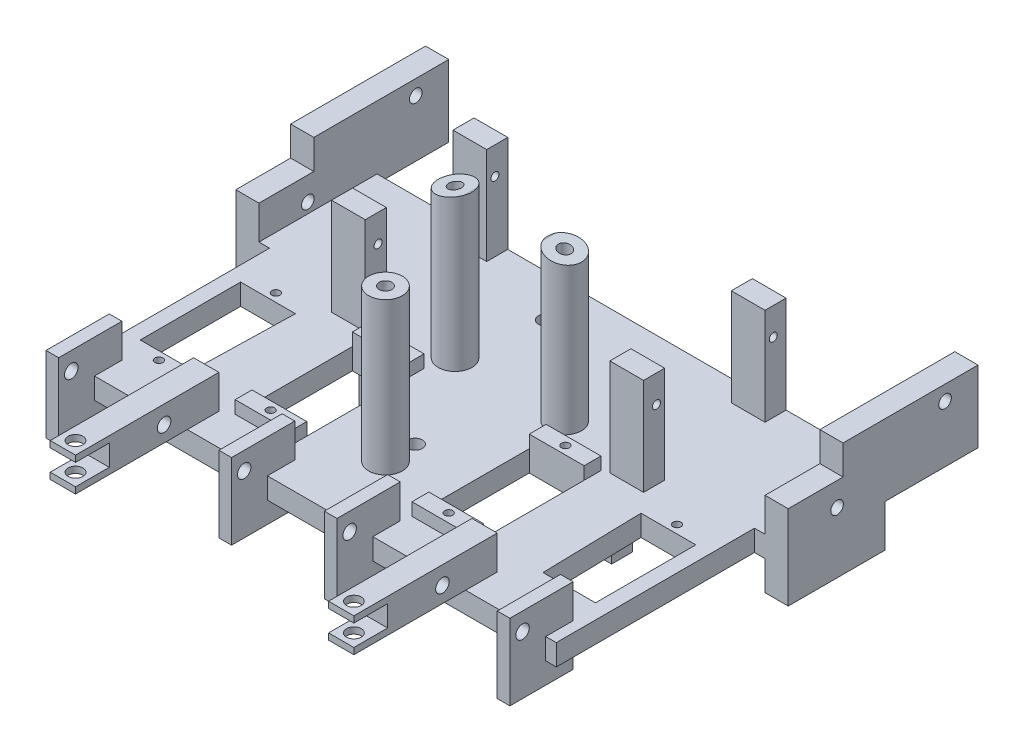
SolidWorks part; units mm, degrees
material "PMMA"
ref_plane "前视基准面" through (0, 0, 0) normal (0, 0, 1) x (1, 0, 0)
ref_plane "上视基准面" through (0, 0, 0) normal (0, 1, 0) x (1, 0, 0)
ref_plane "右视基准面" through (0, 0, 0) normal (1, 0, 0) x (0, 0, -1)
sketch "草图1" plane through (0, 0, 0) normal (0, 1, 0) x (1, 0, 0)
  line L1 (-57.5, 37.5) -> (57.5, 37.5)
  line L2 (-57.5, 37.5) -> (-57.5, -37.5)
  line L3 (-57.5, -37.5) -> (57.5, -37.5)
  line L4 (57.5, 37.5) -> (57.5, -37.5)
  line L5 (-57.5, 37.5) -> (57.5, -37.5) construction
  line L6 (-57.5, -37.5) -> (57.5, 37.5) construction
  point P0 (0, 0)
  dimension "D1" = 115
  dimension "D2" = 75
extrude "凸台-拉伸1" add sketch "草图1" along normal blind 5
sketch "草图4" plane through (0, 5, 0) normal (0, 1, 0) x (1, 0, 0)
  line L1 (-60, 9.5) -> (60, 9.5)
  line L2 (-60, 9.5) -> (-60, 37.5)
  line L3 (-60, 37.5) -> (60, 37.5)
  line L4 (60, 9.5) -> (60, 37.5)
  line L5 (-60, 9.5) -> (60, 37.5) construction
  line L6 (-60, 37.5) -> (60, 9.5) construction
  line L7 (-57.5, -37.5) -> (57.5, -37.5) construction
  point P0 (0, 23.5)
  dimension "D1" = 120
  dimension "D2" = 28
  dimension "D3" = 75
extrude "凸台-拉伸4" add sketch "草图4" against normal blind 5
sketch "草图5" plane through (-60, 0, 0) normal (-1, 0, 0) x (0, 0, 1)
  line L0 (-37.5, 5) -> (-9.5, 5) construction
  line L1 (-9.5, 13) -> (-32.5, 13)
  line L2 (-9.5, 13) -> (-9.5, -7)
  line L3 (-9.5, -7) -> (-32.5, -7)
  line L4 (-32.5, 13) -> (-32.5, -7)
  line L5 (-9.5, 5) -> (-9.5, 0) construction
  dimension "D1" = 8
  dimension "D2" = 23
  dimension "D3" = 20
extrude "凸台-拉伸5" add sketch "草图5" along normal blind 5.5
sketch "草图6" plane through (-60, 0, 0) normal (-1, 0, 0) x (0, 0, 1)
  line L1 (-54.5, 20) -> (-22.5, 20)
  line L2 (-54.5, 20) -> (-54.5, 3)
  line L3 (-54.5, 3) -> (-22.5, 3)
  line L4 (-22.5, 20) -> (-22.5, 3)
  line L5 (-37.5, 5) -> (-32.5, 5) construction
  line L6 (-37.5, 0) -> (-37.5, 5) construction
  dimension "D1" = 15
  dimension "D2" = 17
  dimension "D3" = 32
  dimension "D4" = 17
extrude "凸台-拉伸6" add sketch "草图6" along normal blind 5.5
sketch "草图8" plane through (0, 5, 0) normal (0, 1, 0) x (1, 0, 0)
  line L0 (60, 37.5) -> (-60, 37.5) construction
  line L1 (-37, 37.5) -> (-29, 37.5)
  line L2 (-37, 37.5) -> (-37, 32.5)
  line L3 (-37, 32.5) -> (-29, 32.5)
  line L4 (-29, 37.5) -> (-29, 32.5)
  line L6 (-37, 8.7) -> (-29, 8.7)
  line L7 (-37, 8.7) -> (-37, 3.7)
  line L8 (-37, 3.7) -> (-29, 3.7)
  line L9 (-29, 8.7) -> (-29, 3.7)
  dimension "D1" = 23.8
  dimension "D2" = 37
  dimension "D3" = 8
  dimension "D4" = 5
  dimension "D5" = 5
extrude "凸台-拉伸7" add sketch "草图8" along normal blind 23
sketch "草图9" plane through (0, 5, 0) normal (0, 1, 0) x (1, 0, 0)
  line L1 (-14, -31) -> (-11, -31)
  line L2 (-14, -31) -> (-14, -46)
  line L3 (-14, -46) -> (-11, -46)
  line L4 (-11, -31) -> (-11, -46)
  dimension "D1" = 14
  dimension "D2" = 3
  dimension "D3" = 15
  dimension "D4" = 46
extrude "凸台-拉伸8" add sketch "草图9" along normal blind 8 and the other way blind 10
sketch "草图10" plane through (0, 5, 0) normal (0, 1, 0) x (1, 0, 0)
  line L0 (-14, -31) -> (-14, -46) construction
  line L1 (-55, -31) -> (-52, -31)
  line L2 (-55, -31) -> (-55, -46)
  line L3 (-55, -46) -> (-52, -46)
  line L4 (-52, -31) -> (-52, -46)
  line L6 (-11, -31) -> (-14, -31) construction
  line L7 (-14, -46) -> (-11, -46) construction
  dimension "D1" = 38
extrude "凸台-拉伸9" add sketch "草图10" along normal blind 8 and the other way blind 10
sketch "草图11" plane through (0, 5, 0) normal (0, 1, 0) x (1, 0, 0)
  line L1 (-36, -30) -> (-30, -30)
  line L2 (-36, -30) -> (-36, -64)
  line L3 (-36, -64) -> (-30, -64)
  line L4 (-30, -30) -> (-30, -64)
  dimension "D1" = 6
  dimension "D2" = 34
  dimension "D3" = 64
  dimension "D4" = 30
extrude "凸台-拉伸10" add sketch "草图11" along normal blind 8
sketch "草图12" plane through (0, 5, 0) normal (0, 1, 0) x (1, 0, 0)
  circle A0 centre (-13, 9) radius 4
  dimension "D1" = 13
  dimension "D2" = 9
  dimension "D3" = 8
extrude "凸台-拉伸11" add sketch "草图12" along normal blind 36
sketch "草图19" plane through (-37, 0, 0) normal (-1, 0, 0) x (0, 0, 1)
  line L1 (-8.7, 28) -> (-8.7, 5) construction
  line L2 (-8.7, 28) -> (-3.7, 28) construction
  line L3 (-32.5, 28) -> (-32.5, 5) construction
  circle A0 centre (-6.75, 21.5) radius 0.95
  circle A1 centre (-34.45, 21.5) radius 0.95
  dimension "D1" = 6.5
  dimension "D2" = 1.95
  dimension "D3" = 1.9
  dimension "D4" = 27.7
  dimension "D5" = 1.9
  dimension "D6" = 1.95
extrude "切除-拉伸8" cut sketch "草图19" against normal up to next
sketch "草图25" plane through (0, 5, 0) normal (0, 1, 0) x (1, 0, 0)
  circle A0 centre (0, -20.5) radius 4
  circle A1 centre (-13, 9) radius 4 construction
  dimension "D1" = 20.5
extrude "凸台-拉伸14" add sketch "草图25" along normal blind 36
sketch "草图26" plane through (0, 0, 0) normal (0, 0, 1) x (1, 0, 0)
  line L0 (-17, 41) -> (-17, 39.644)
  line L1 (-17, 41) -> (-17, 5) construction
  line L2 (-17, 39.644) -> (-9.31, 41)
  line L3 (-9, 41) -> (-17, 41) construction
  line L4 (-9.31, 41) -> (-17, 41)
  dimension "D1" = 10
  dimension "D2" = 0.31
extrude "切除-拉伸14" cut sketch "草图26" against normal blind 36
sketch "草图28" plane through (0, 0, 64) normal (0, 0, 1) x (1, 0, 0)
  line L0 (-36, 13) -> (-36, 5) construction
  line L1 (-36, 11.5) -> (-30, 11.5)
  line L2 (-36, 11.5) -> (-36, 6.5)
  line L3 (-36, 6.5) -> (-30, 6.5)
  line L4 (-30, 11.5) -> (-30, 6.5)
  line L5 (-30, 13) -> (-30, 5) construction
  line L6 (-36, 13) -> (-30, 13) construction
  dimension "D1" = 1.5
  dimension "D2" = 5
extrude "切除-拉伸16" cut sketch "草图28" against normal blind 8
sketch "草图29" plane through (0, 13, 0) normal (0, 1, 0) x (1, 0, 0)
  line L0 (-36, -64) -> (-30, -64) construction
  circle A0 centre (-33, -61) radius 1.75
  point P5 (-33, -64)
  dimension "D1" = 3
  dimension "D2" = 3.5
extrude "切除-拉伸17" cut sketch "草图29" against normal blind 8
sketch "草图30" plane through (-55, 0, 0) normal (-1, 0, 0) x (0, 0, 1)
  line L0 (31, 5) -> (37.5, 5) construction
  circle A0 centre (43, 8.75) radius 1.6
  dimension "D1" = 43
  dimension "D2" = 3.75
  dimension "D3" = 3.2
extrude "切除-拉伸18" cut sketch "草图30" against normal blind 48
sketch "草图31" plane through (0, 5, 0) normal (0, 1, 0) x (1, 0, 0)
  circle A0 centre (0, -13.5) radius 1.75
  circle A1 centre (-10, 27.5) radius 1.75
  circle A2 centre (10, 27.5) radius 1.75
  dimension "D1" = 20
  dimension "D2" = 10
  dimension "D3" = 27.5
  dimension "D4" = 3.5
  dimension "D5" = 3.5
  dimension "D7" = 3.5
  dimension "D6" = 13.5
extrude "切除-拉伸19" cut sketch "草图31" against normal blind 20
sketch "草图35" plane through (-65.5, 0, 0) normal (-1, 0, 0) x (0, 0, 1)
  circle A0 centre (-46.6884, 16.4527) radius 1.5
  circle A1 centre (-21.0894, 7.4378) radius 1.5
  dimension "D1" = 3
  dimension "D2" = 3
extrude "切除-拉伸23" cut sketch "草图35" against normal blind 15
sketch "草图36" plane through (0, 5, 0) normal (0, 1, 0) x (1, 0, 0)
  line L0 (-21.1079, 3.9238) -> (-21.1079, -28.1166) construction
  line L1 (-27.473, -0.8803) -> (-14.473, -0.8803)
  line L2 (-27.473, -0.8803) -> (-27.473, -24.6803)
  line L3 (-27.473, -24.6803) -> (-14.473, -24.6803)
  line L4 (-14.473, -0.8803) -> (-14.473, -24.6803)
  line L5 (-40.9739, -0.8803) -> (-41.5361, -24.6803)
  line L6 (-47.6088, 4.4682) -> (-47.6088, -27.5723) construction
  line L7 (-53.9739, -24.6803) -> (-41.5361, -24.6803)
  line L8 (-53.9739, -0.8803) -> (-53.9739, -24.6803)
  line L9 (-53.9739, -0.8803) -> (-40.9739, -0.8803)
  circle A0 centre (-21.1079, 1.0697) radius 0.95
  circle A1 centre (-21.1079, -26.6303) radius 0.95
  circle A2 centre (-47.6088, -26.6303) radius 0.95
  circle A3 centre (-47.5597, 1.0697) radius 0.95
  dimension "D3" = 1.9
  dimension "D4" = 1.9
  dimension "D9" = 1.9
  dimension "D10" = 1.9
  dimension "D1" = 23.8
  dimension "D2" = 13
  dimension "D5" = 1.95
  dimension "D6" = 1.95
  dimension "D7" = 23.8
  dimension "D8" = 13
  dimension "D11" = 1.95
  dimension "D12" = 1.95
extrude "切除-拉伸24" cut sketch "草图36" against normal blind 7
sketch "草图37" plane through (0, 0, 0) normal (0, -1, 0) x (1, 0, 0)
  line L1 (-23.9346, -36.9825) -> (-29.9346, -36.9825)
  line L2 (-23.9346, -36.9825) -> (-23.9346, -31.9825)
  line L3 (-23.9346, -31.9825) -> (-29.9346, -31.9825)
  line L4 (-29.9346, -36.9825) -> (-29.9346, -31.9825)
  line L5 (-23.9346, -8.1825) -> (-29.9346, -8.1825)
  line L6 (-23.9346, -8.1825) -> (-23.9346, -3.1825)
  line L7 (-23.9346, -3.1825) -> (-29.9346, -3.1825)
  line L8 (-29.9346, -8.1825) -> (-29.9346, -3.1825)
  dimension "D1" = 23.8
  dimension "D2" = 6
  dimension "D3" = 5
  dimension "D4" = 5
extrude "凸台-拉伸15" add sketch "草图37" along normal blind 13
sketch "草图38" plane through (-29.9346, 0, 0) normal (-1, 0, 0) x (0, 0, 1)
  line L0 (-31.9825, -13) -> (-31.9825, 0) construction
  line L2 (-37.5, 0) -> (-32.5, 0) construction
  line L3 (-20.0825, 2.1642) -> (-20.0825, -15.8009) construction
  circle A0 centre (-33.9325, -4.5) radius 0.95
  circle A1 centre (-6.2325, -4.5) radius 0.95
  dimension "D1" = 1.9
  dimension "D2" = 1.95
  dimension "D3" = 4.5
  dimension "D4" = 11.9
extrude "切除-拉伸25" cut sketch "草图38" against normal blind 13
sketch "草图43" plane through (0, 0, 0) normal (0, -1, 0) x (1, 0, 0)
  line L0 (60, -37.5) -> (-60, -37.5) construction
  line L1 (-53.9346, -1.1825) -> (-15.9346, -1.1825)
  line L2 (-53.9346, -1.1825) -> (-53.9346, -37.5)
  line L3 (-53.9346, -37.5) -> (-15.9346, -37.5)
  line L4 (-15.9346, -1.1825) -> (-15.9346, -37.5)
  line L5 (-23.9346, -3.1825) -> (-29.9346, -3.1825) construction
  line L6 (-23.9346, -8.1825) -> (-23.9346, -3.1825) construction
  line L7 (-23.9346, -3.1825) -> (-29.9346, -3.1825) construction
  line L8 (-29.9346, -3.1825) -> (-29.9346, -8.1825) construction
  line L9 (-29.9346, -8.1825) -> (-23.9346, -8.1825) construction
  line L10 (-23.9346, -36.9825) -> (-23.9346, -31.9825) construction
  line L11 (-23.9346, -31.9825) -> (-29.9346, -31.9825) construction
  line L12 (-29.9346, -31.9825) -> (-29.9346, -36.9825) construction
  line L13 (-29.9346, -36.9825) -> (-23.9346, -36.9825) construction
  line L14 (-23.9346, -8.1825) -> (-23.9346, -3.1825)
  line L15 (-23.9346, -3.1825) -> (-29.9346, -3.1825)
  line L16 (-29.9346, -3.1825) -> (-29.9346, -8.1825)
  line L17 (-29.9346, -8.1825) -> (-23.9346, -8.1825)
  line L18 (-23.9346, -36.9825) -> (-23.9346, -31.9825)
  line L19 (-23.9346, -31.9825) -> (-29.9346, -31.9825)
  line L20 (-29.9346, -31.9825) -> (-29.9346, -36.9825)
  line L21 (-29.9346, -36.9825) -> (-23.9346, -36.9825)
  dimension "D1" = 2
  dimension "D2" = 8
  dimension "D3" = 24
extrude "切除-拉伸28" cut sketch "草图43" against normal blind 2
sketch "草图41" plane through (0, 5, 0) normal (0, 1, 0) x (1, 0, 0)
  line L0 (-27.473, -0.8803) -> (-27.473, -24.6803) construction
  line L1 (-14.473, -0.8803) -> (-27.473, -0.8803)
  line L2 (-14.473, -0.8803) -> (-14.473, 3.1197)
  line L3 (-14.473, 3.1197) -> (-27.473, 3.1197)
  line L4 (-27.473, -0.8803) -> (-27.473, 3.1197)
  line L5 (-14.473, -24.6803) -> (-14.473, -0.8803) construction
  line L6 (-27.473, -24.6803) -> (-14.473, -24.6803)
  line L7 (-27.473, -24.6803) -> (-27.473, -28.6803)
  line L8 (-27.473, -28.6803) -> (-14.473, -28.6803)
  line L9 (-14.473, -24.6803) -> (-14.473, -28.6803)
  circle A0 centre (-21.1079, 1.0697) radius 0.95
  circle A1 centre (-21.1079, -26.6303) radius 0.95
  dimension "D3" = 1.9
  dimension "D4" = 1.9
  dimension "D1" = 4
  dimension "D2" = 4
extrude "凸台-拉伸16" add sketch "草图41" along normal blind 3
sketch "草图39" plane through (0, 5, 0) normal (0, 1, 0) x (1, 0, 0)
  circle A0 centre (-13, 9) radius 1.5
  circle A1 centre (0, -20.5) radius 1.5
  dimension "D1" = 3
  dimension "D2" = 3
extrude "切除-拉伸26" cut sketch "草图39" against normal blind 13 and the other way blind 42
mirror "镜向1" about plane through (0, 0, 0) normal (1, 0, 0) of "凸台-拉伸5", "凸台-拉伸6", "凸台-拉伸7", "凸台-拉伸8", "凸台-拉伸9", "凸台-拉伸10", "凸台-拉伸11", "切除-拉伸8", "切除-拉伸14", "切除-拉伸16", "切除-拉伸17", "切除-拉伸18", "切除-拉伸23", "切除-拉伸24", "凸台-拉伸15", "切除-拉伸25", "切除-拉伸28", "凸台-拉伸16", "切除-拉伸26"
